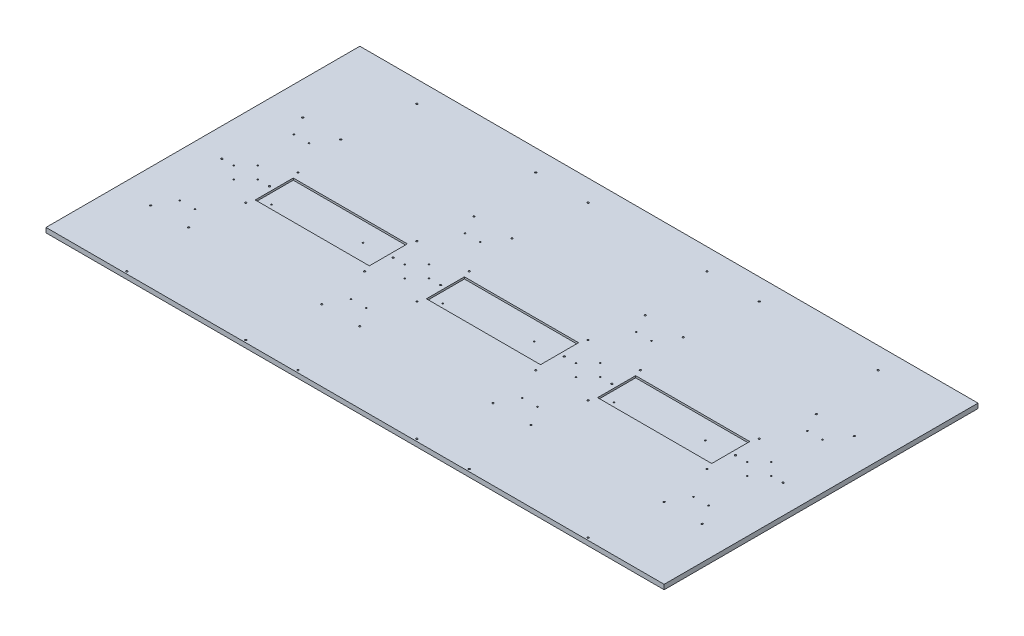
SolidWorks part; units mm, degrees
ref_plane "Front" through (0, 0, 0) normal (0, 0, 1) x (1, 0, 0)
ref_plane "Top" through (0, 0, 0) normal (0, 1, 0) x (1, 0, 0)
ref_plane "Right" through (0, 0, 0) normal (1, 0, 0) x (0, 0, -1)
sketch "Sketch1" plane through (0, 0, 0) normal (0, 1, 0) x (1, 0, 0)
  line L1 (0, 0) -> (800.1, 0)
  line L2 (0, 0) -> (0, 419.1)
  line L3 (0, 419.1) -> (800.1, 419.1)
  line L4 (800.1, 0) -> (800.1, 419.1)
  dimension "D1" = 419.1
  dimension "D2" = 800.1
extrude "Boss-Extrude1" add sketch "Sketch1" along normal blind 6.35
sketch "Sketch2" plane through (0, 6.35, 0) normal (0, 1, 0) x (1, 0, 0)
  line L0 (0, 0) -> (800.1, 0) construction
  line L1 (0, 419.1) -> (25.4, 419.1)
  line L2 (0, 419.1) -> (0, 0)
  line L3 (0, 0) -> (25.4, 0)
  line L4 (25.4, 419.1) -> (25.4, 0)
  line L5 (88.9, 165.1) -> (254, 165.1)
  line L6 (25.4, 419.1) -> (88.9, 419.1)
  line L7 (25.4, 419.1) -> (25.4, 0)
  line L8 (25.4, 0) -> (88.9, 0)
  line L9 (88.9, 419.1) -> (88.9, 0)
  line L10 (88.9, 0) -> (254, 0)
  line L11 (88.9, 0) -> (88.9, 165.1)
  line L12 (88.9, 165.1) -> (254, 165.1)
  line L13 (254, 0) -> (254, 165.1)
  line L14 (88.9, 165.1) -> (88.9, 228.6)
  line L15 (254, 165.1) -> (254, 228.6)
  line L16 (88.9, 228.6) -> (254, 228.6)
  line L17 (88.9, 228.6) -> (254, 228.6)
  line L18 (88.9, 228.6) -> (88.9, 393.7)
  line L19 (254, 228.6) -> (254, 393.7)
  line L20 (88.9, 393.7) -> (254, 393.7)
  line L21 (317.5, 419.1) -> (317.5, 0)
  line L22 (254, 419.1) -> (254, 0)
  line L23 (254, 419.1) -> (317.5, 419.1)
  line L24 (254, 0) -> (317.5, 0)
  line L25 (317.5, 228.6) -> (482.6, 228.6)
  line L26 (317.5, 228.6) -> (317.5, 393.7)
  line L27 (317.5, 393.7) -> (482.6, 393.7)
  line L28 (482.6, 228.6) -> (482.6, 393.7)
  line L29 (317.5, 165.1) -> (482.6, 165.1)
  line L30 (317.5, 165.1) -> (317.5, 228.6)
  line L31 (317.5, 228.6) -> (482.6, 228.6)
  line L32 (482.6, 165.1) -> (482.6, 228.6)
  line L33 (317.5, 0) -> (317.5, 165.1)
  line L34 (317.5, 0) -> (482.6, 0)
  line L35 (482.6, 0) -> (482.6, 165.1)
  line L36 (317.5, 165.1) -> (482.6, 165.1)
  line L37 (546.1, 419.1) -> (546.1, 0)
  line L38 (482.6, 419.1) -> (482.6, 0)
  line L39 (482.6, 419.1) -> (546.1, 419.1)
  line L40 (482.6, 0) -> (546.1, 0)
  line L41 (546.1, 228.6) -> (711.2, 228.6)
  line L42 (546.1, 228.6) -> (546.1, 393.7)
  line L43 (546.1, 393.7) -> (711.2, 393.7)
  line L44 (711.2, 228.6) -> (711.2, 393.7)
  line L45 (546.1, 165.1) -> (711.2, 165.1)
  line L46 (546.1, 165.1) -> (546.1, 228.6)
  line L47 (546.1, 228.6) -> (711.2, 228.6)
  line L48 (711.2, 165.1) -> (711.2, 228.6)
  line L49 (546.1, 0) -> (546.1, 165.1)
  line L50 (546.1, 0) -> (711.2, 0)
  line L51 (711.2, 0) -> (711.2, 165.1)
  line L52 (546.1, 165.1) -> (711.2, 165.1)
  line L53 (800.1, 419.1) -> (0, 419.1) construction
  line L54 (711.2, 0) -> (774.7, 0)
  line L55 (711.2, 0) -> (711.2, 419.1)
  line L56 (711.2, 419.1) -> (774.7, 419.1)
  line L57 (774.7, 0) -> (774.7, 419.1)
  line L58 (254, 196.85) -> (25.4, 196.85) construction
  line L59 (107.95, 228.6) -> (234.95, 228.6)
  line L60 (107.95, 228.6) -> (107.95, 368.3)
  line L61 (107.95, 368.3) -> (234.95, 368.3)
  line L62 (234.95, 228.6) -> (234.95, 368.3)
  line L63 (107.95, 25.4) -> (234.95, 25.4)
  line L64 (234.95, 165.1) -> (234.95, 25.4)
  line L65 (107.95, 165.1) -> (234.95, 165.1)
  line L66 (107.95, 165.1) -> (107.95, 25.4)
  line L67 (336.55, 228.6) -> (336.55, 368.3)
  line L68 (336.55, 228.6) -> (463.55, 228.6)
  line L69 (463.55, 228.6) -> (463.55, 368.3)
  line L70 (336.55, 368.3) -> (463.55, 368.3)
  line L71 (336.55, 25.4) -> (463.55, 25.4)
  line L72 (463.55, 165.1) -> (463.55, 25.4)
  line L73 (336.55, 165.1) -> (463.55, 165.1)
  line L74 (336.55, 165.1) -> (336.55, 25.4)
  line L75 (565.15, 228.6) -> (565.15, 368.3)
  line L76 (565.15, 228.6) -> (692.15, 228.6)
  line L77 (692.15, 228.6) -> (692.15, 368.3)
  line L78 (565.15, 368.3) -> (692.15, 368.3)
  line L79 (565.15, 25.4) -> (692.15, 25.4)
  line L80 (692.15, 165.1) -> (692.15, 25.4)
  line L81 (565.15, 165.1) -> (692.15, 165.1)
  line L82 (565.15, 165.1) -> (565.15, 25.4)
  dimension "D1" = 25.4
  dimension "D2" = 63.5
  dimension "D3" = 165.1
  dimension "D4" = 165.1
  dimension "D5" = 63.5
  dimension "D6" = 165.1
  dimension "D8" = 63.5
  dimension "D9" = 127
  dimension "D10" = 19.05
  dimension "D11" = 25.4
  dimension "D7" = 3
  dimension "D12" = 3
sketch "Sketch6" plane through (0, 6.35, 0) normal (0, 1, 0) x (1, 0, 0)
  line L0 (0, 419.1) -> (0, 0)
  line L1 (0, 419.1) -> (-12.7, 419.1)
  line L2 (0, 0) -> (-12.7, 0)
  line L3 (-12.7, 419.1) -> (-12.7, 0)
  line L4 (800.1, 419.1) -> (800.1, 0)
  line L5 (800.1, 419.1) -> (812.8, 419.1)
  line L6 (800.1, 0) -> (812.8, 0)
  line L7 (812.8, 419.1) -> (812.8, 0)
  dimension "D1" = 12.7
  dimension "D2" = 12.7
extrude "Boss-Extrude2" add sketch "Sketch6" against normal blind 6.35
sketch "Sketch4" plane through (0, 6.35, 0) normal (0, 1, 0) x (1, 0, 0)
  line L0 (88.9, 393.7) -> (254, 393.7) construction
  line L1 (88.9, 419.1) -> (88.9, 0) construction
  line L2 (88.9, 393.7) -> (254, 228.6) construction
  line L3 (254, 228.6) -> (254, 393.7) construction
  line L4 (254, 393.7) -> (88.9, 228.6) construction
  line L5 (254, 311.15) -> (101.6, 311.15) construction
  circle A0 centre (92.075, 390.525) radius 1.1303
  circle A1 centre (250.825, 231.775) radius 1.1303
  circle A2 centre (250.825, 390.525) radius 1.1303
  circle A3 centre (92.075, 231.775) radius 1.1303
  circle A4 centre (320.675, 390.525) radius 1.1303
  circle A5 centre (320.675, 231.775) radius 1.1303
  circle A6 centre (479.425, 231.775) radius 1.1303
  circle A7 centre (479.425, 390.525) radius 1.1303
  circle A8 centre (549.275, 390.525) radius 1.1303
  circle A9 centre (549.275, 231.775) radius 1.1303
  circle A10 centre (708.025, 231.775) radius 1.1303
  circle A11 centre (708.025, 390.525) radius 1.1303
  circle A12 centre (320.675, 161.925) radius 1.1303
  circle A13 centre (320.675, 3.175) radius 1.1303
  circle A14 centre (479.425, 3.175) radius 1.1303
  circle A15 centre (479.425, 161.925) radius 1.1303
  circle A16 centre (549.275, 161.925) radius 1.1303
  circle A17 centre (549.275, 3.175) radius 1.1303
  circle A18 centre (708.025, 3.175) radius 1.1303
  circle A19 centre (708.025, 161.925) radius 1.1303
  circle A20 centre (92.075, 161.925) radius 1.1303
  circle A21 centre (92.075, 3.175) radius 1.1303
  circle A22 centre (250.825, 3.175) radius 1.1303
  circle A23 centre (250.825, 161.925) radius 1.1303
  dimension "D1" = 2.2606
  dimension "D2" = 3.175
  dimension "D3" = 3.175
  dimension "D4" = 3
  dimension "D5" = 2
extrude "Cut-Extrude1" cut sketch "Sketch4" against normal through all both and the other way through all
sketch "Sketch5" plane through (0, 6.35, 0) normal (0, 1, 0) x (1, 0, 0)
  line L0 (57.15, 0) -> (57.15, 419.1) construction
  line L1 (25.4, 0) -> (88.9, 0) construction
  line L2 (25.4, 419.1) -> (88.9, 419.1) construction
  line L3 (88.9, 228.6) -> (88.9, 165.1) construction
  line L4 (88.9, 165.1) -> (26.9154, 196.85) construction
  line L5 (26.9154, 196.85) -> (88.9, 196.85) construction
  line L6 (88.9, 165.1) -> (254, 165.1) construction
  line L8 (88.9, 228.6) -> (254, 228.6) construction
  circle A0 centre (82.55, 95.25) radius 1.1303
  circle A1 centre (31.75, 95.25) radius 1.1303
  circle A2 centre (82.55, 298.45) radius 1.1303
  circle A3 centre (31.75, 298.45) radius 1.1303
  circle A4 centre (88.9, 196.85) radius 1.1303
  circle A5 centre (25.4, 196.85) radius 1.1303
  circle A6 centre (254, 196.85) radius 1.1303
  circle A7 centre (317.5, 196.85) radius 1.1303
  circle A8 centre (260.35, 95.25) radius 1.1303
  circle A9 centre (311.15, 95.25) radius 1.1303
  circle A10 centre (260.35, 298.45) radius 1.1303
  circle A11 centre (311.15, 298.45) radius 1.1303
  circle A12 centre (482.6, 196.85) radius 1.1303
  circle A13 centre (546.1, 196.85) radius 1.1303
  circle A14 centre (488.95, 95.25) radius 1.1303
  circle A15 centre (539.75, 95.25) radius 1.1303
  circle A16 centre (488.95, 298.45) radius 1.1303
  circle A17 centre (539.75, 298.45) radius 1.1303
  circle A18 centre (711.2, 196.85) radius 1.1303
  circle A19 centre (774.7, 196.85) radius 1.1303
  circle A20 centre (717.55, 95.25) radius 1.1303
  circle A21 centre (768.35, 95.25) radius 1.1303
  circle A22 centre (717.55, 298.45) radius 1.1303
  circle A23 centre (768.35, 298.45) radius 1.1303
  point P13 (57.15, 209.55)
  dimension "D1" = 2.2606
  dimension "D2" = 25.4
  dimension "D3" = 101.6
  dimension "D4" = 2.2606
  dimension "D5" = 31.75
  dimension "D6" = 31.75
  dimension "D7" = 2.2606
  dimension "D8" = 31.75
  dimension "D9" = 31.75
  dimension "D10" = 4
extrude "Cut-Extrude2" cut sketch "Sketch5" against normal through all
sketch "Sketch7" plane through (0, 6.35, 0) normal (0, 1, 0) x (1, 0, 0)
  line L0 (95.25, 196.85) -> (247.65, 196.85) construction
  line L1 (95.25, 222.25) -> (247.65, 222.25)
  line L2 (95.25, 222.25) -> (95.25, 171.45)
  line L3 (95.25, 171.45) -> (247.65, 171.45)
  line L4 (247.65, 222.25) -> (247.65, 171.45)
  line L5 (247.65, 196.85) -> (171.45, 222.25) construction
  line L6 (171.45, 222.25) -> (171.45, 171.45) construction
  line L7 (88.9, 419.1) -> (88.9, 0) construction
  line L8 (88.9, 228.6) -> (254, 228.6) construction
  line L9 (323.85, 222.25) -> (323.85, 171.45)
  line L10 (323.85, 222.25) -> (476.25, 222.25)
  line L11 (476.25, 222.25) -> (476.25, 171.45)
  line L12 (323.85, 171.45) -> (476.25, 171.45)
  line L13 (552.45, 222.25) -> (552.45, 171.45)
  line L14 (552.45, 222.25) -> (704.85, 222.25)
  line L15 (704.85, 222.25) -> (704.85, 171.45)
  line L16 (552.45, 171.45) -> (704.85, 171.45)
  dimension "D1" = 152.4
  dimension "D2" = 50.8
  dimension "D3" = 82.55
  dimension "D4" = 31.75
  dimension "D5" = 3
extrude "Cut-Extrude3" cut sketch "Sketch7" against normal blind 2.54
sketch "Sketch8" plane through (0, 3.81, 0) normal (0, 1, 0) x (1, 0, 0)
  line L0 (98.933, 196.85) -> (243.967, 196.85) construction
  line L1 (98.933, 174.625) -> (243.967, 174.625)
  line L2 (98.933, 174.625) -> (98.933, 219.075)
  line L3 (98.933, 219.075) -> (243.967, 219.075)
  line L4 (243.967, 174.625) -> (243.967, 219.075)
  line L5 (243.967, 196.85) -> (171.45, 174.625) construction
  line L6 (171.45, 174.625) -> (171.45, 219.075) construction
  line L7 (95.25, 222.25) -> (95.25, 171.45) construction
  line L8 (95.25, 171.45) -> (247.65, 171.45) construction
  circle A0 centre (109.1689, 179.451) radius 0.889
  circle A1 centre (214.249, 196.469) radius 0.889
  circle A2 centre (442.849, 196.469) radius 0.889
  circle A3 centre (337.7689, 179.451) radius 0.889
  circle A4 centre (671.449, 196.469) radius 0.889
  circle A5 centre (566.3689, 179.451) radius 0.889
  dimension "D5" = 1.778
  dimension "D6" = 4.826
  dimension "D7" = 10.2359
  dimension "D8" = 1.778
  dimension "D9" = 115.316
  dimension "D10" = 21.844
  dimension "D1" = 44.45
  dimension "D2" = 145.034
  dimension "D3" = 76.2
  dimension "D4" = 25.4
  dimension "D11" = 3
extrude "Cut-Extrude5" cut sketch "Sketch8" against normal through all contours A3 | A5 | A4 | A1 | A0 | A2
sketch "Sketch9" plane through (0, 6.35, 0) normal (0, 1, 0) x (1, 0, 0)
  line L0 (25.4, 196.85) -> (88.9, 196.85) construction
  line L1 (88.9, 419.1) -> (88.9, 0) construction
  line L2 (254, 196.85) -> (25.4, 196.85) construction
  circle A0 centre (40.9856, 196.85) radius 0.889
  circle A1 centre (57.15, 213.0144) radius 0.889
  circle A2 centre (73.3144, 196.85) radius 0.889
  circle A3 centre (57.15, 180.6856) radius 0.889
  circle A4 centre (269.5856, 196.85) radius 0.889
  circle A5 centre (285.75, 213.0144) radius 0.889
  circle A6 centre (301.9144, 196.85) radius 0.889
  circle A7 centre (285.75, 180.6856) radius 0.889
  circle A8 centre (498.1856, 196.85) radius 0.889
  circle A9 centre (514.35, 213.0144) radius 0.889
  circle A10 centre (530.5144, 196.85) radius 0.889
  circle A11 centre (514.35, 180.6856) radius 0.889
  circle A12 centre (726.7856, 196.85) radius 0.889
  circle A13 centre (742.95, 213.0144) radius 0.889
  circle A14 centre (759.1144, 196.85) radius 0.889
  circle A15 centre (742.95, 180.6856) radius 0.889
  point P10 (57.15, 196.85)
  point P19 (57.15, 196.85)
  dimension "D1" = 1.778
  dimension "D2" = 16.1644
  dimension "D3" = 4
  dimension "D4" = 4
extrude "Cut-Extrude6" cut sketch "Sketch9" against normal through all
sketch "Sketch10" plane through (0, 6.35, 0) normal (0, 1, 0) x (1, 0, 0)
  line L0 (31.75, 298.45) -> (79.1635, 298.45) construction
  line L1 (55.4568, 298.45) -> (55.4568, 273.9615) construction
  line L2 (25.4, 196.85) -> (88.9, 196.85) construction
  circle A0 centre (45.2968, 273.05) radius 0.889
  circle A1 centre (65.6168, 273.05) radius 0.889
  circle A2 centre (65.6168, 120.65) radius 0.889
  circle A3 centre (45.2968, 120.65) radius 0.889
  circle A4 centre (273.8968, 120.65) radius 0.889
  circle A5 centre (294.2168, 120.65) radius 0.889
  circle A6 centre (273.8968, 273.05) radius 0.889
  circle A7 centre (294.2168, 273.05) radius 0.889
  circle A8 centre (502.4968, 120.65) radius 0.889
  circle A9 centre (522.8168, 120.65) radius 0.889
  circle A10 centre (502.4968, 273.05) radius 0.889
  circle A11 centre (522.8168, 273.05) radius 0.889
  circle A12 centre (731.0968, 120.65) radius 0.889
  circle A13 centre (751.4168, 120.65) radius 0.889
  circle A14 centre (731.0968, 273.05) radius 0.889
  circle A15 centre (751.4168, 273.05) radius 0.889
  dimension "D1" = 25.4
  dimension "D3" = 1.778
  dimension "D2" = 10.16
  dimension "D4" = 4
extrude "Cut-Extrude7" cut sketch "Sketch10" against normal through all
